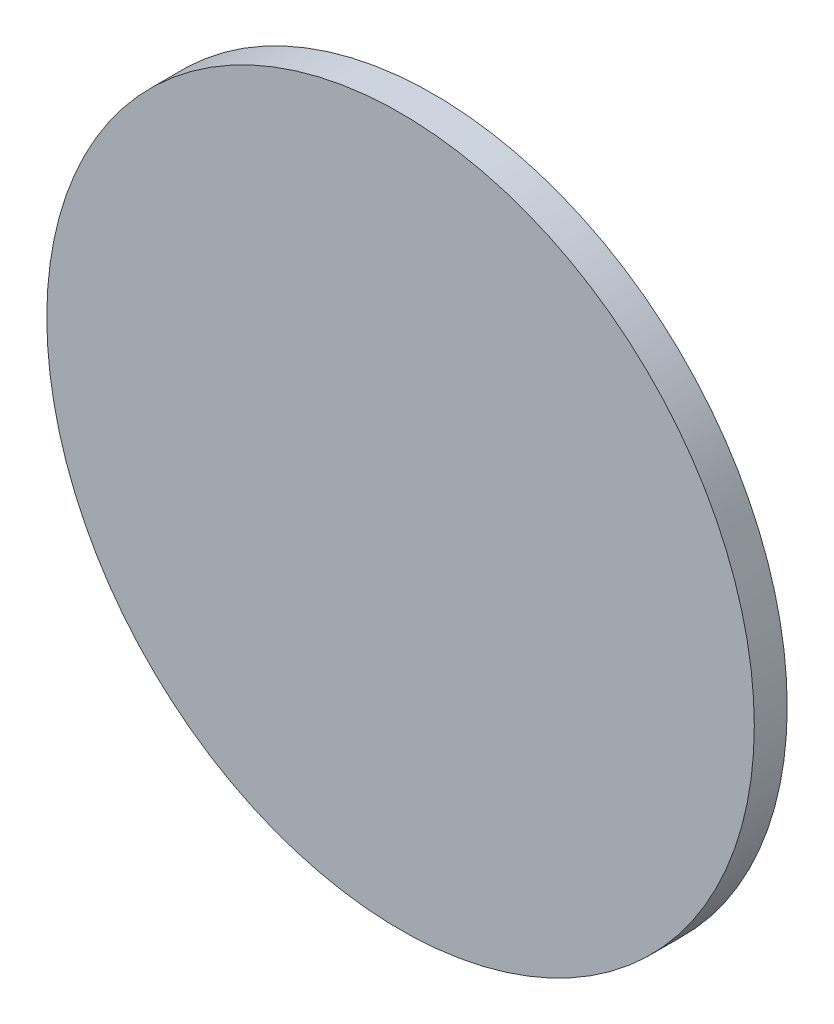
SolidWorks part; units mm, degrees
ref_plane "前视基准面" through (0, 0, 0) normal (0, 0, 1) x (1, 0, 0)
ref_plane "上视基准面" through (0, 0, 0) normal (0, 1, 0) x (1, 0, 0)
ref_plane "右视基准面" through (0, 0, 0) normal (1, 0, 0) x (0, 0, -1)
sketch "草图2" plane through (0, 0, 0) normal (0, 0, 1) x (1, 0, 0)
  circle A0 centre (0, 0) radius 43
  dimension "D1" = 86
extrude "凸台-拉伸1" add sketch "草图2" along normal blind 4
